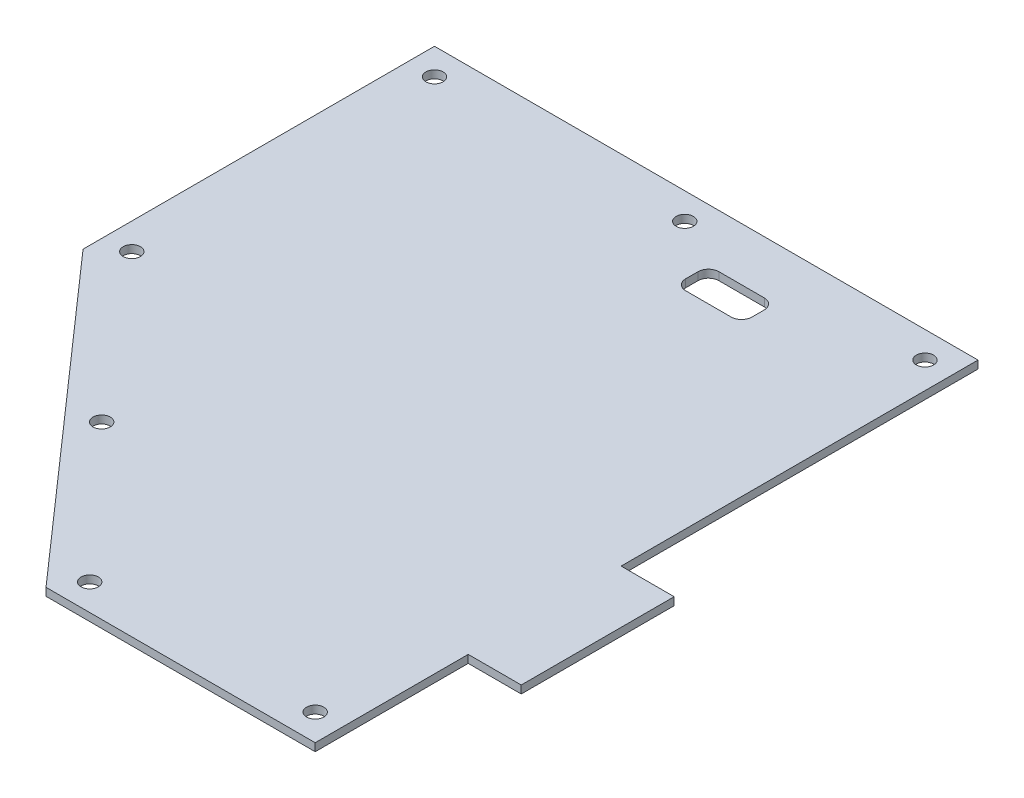
SolidWorks part; units mm, degrees
ref_plane "Front Plane" through (0, 0, 0) normal (0, 0, 1) x (1, 0, 0)
ref_plane "Top Plane" through (0, 0, 0) normal (0, 1, 0) x (1, 0, 0)
ref_plane "Right Plane" through (0, 0, 0) normal (1, 0, 0) x (0, 0, -1)
sketch "Sketch1" plane through (0, 0, 0) normal (0, 1, 0) x (1, 0, 0)
  line L0 (0, 0) -> (104.14, 0)
  line L2 (0, 0) -> (0, -67.34)
  line L4 (104.1401, -97.6797) -> (104.1401, -126.9997)
  line L5 (104.1401, -126.9997) -> (52.5601, -126.9997)
  line L6 (0, -67.34) -> (52.5601, -126.9997)
  line L8 (114.3001, -97.6797) -> (114.3001, -68.3797)
  line L11 (104.14, 0) -> (104.1401, -68.3797)
  line L12 (104.1401, -97.6797) -> (114.3001, -97.6797)
  line L13 (104.1401, -68.3797) -> (114.3001, -68.3797)
  dimension "D1" = 104.14
  dimension "D2" = 138.62
  dimension "D3" = 67.34
  dimension "D5" = 29.32
  dimension "D6" = 51.58
  dimension "D8" = 29.3
  dimension "D9" = 79.51
extrude "Boss-Extrude1" add sketch "Sketch1" along normal blind 1.5
sketch "Sketch2" plane through (0, 1.5, 0) normal (0, 1, 0) x (1, 0, 0)
  line L2 (104.1401, -126.9997) -> (104.1401, -97.6797) construction
  line L3 (52.5601, -126.9997) -> (104.1401, -126.9997) construction
  line L5 (104.14, 0) -> (0, 0) construction
  line L6 (0, 0) -> (0, -67.34) construction
  line L7 (0, -67.34) -> (52.5601, -126.9997) construction
  line L8 (104.1401, -68.3797) -> (104.14, 0) construction
  point P5 (99.0601, -121.9197)
  point P10 (55.8501, -121.9197)
  point P11 (99.06, -5.08)
  point P16 (5.08, -5.08)
  point P19 (53.03, -5.08)
  point P20 (5.08, -63.08)
  point P23 (30.4656, -94.2361)
  dimension "D2" = 5.08
  dimension "D3" = 5.08
  dimension "D4" = 5.08
  dimension "D5" = 43.21
  dimension "D6" = 5.08
  dimension "D8" = 5.08
  dimension "D9" = 5.08
  dimension "D10" = 5.08
  dimension "D11" = 47.95
  dimension "D12" = 58
  dimension "D13" = 5.08
  dimension "D14" = 37.56
  dimension "D15" = 5.08
hole_wizard "Ø4.0mm Dowel Hole1" positions "3DSketch1" profile "Sketch3" hole size "Ø4.0" standard "ANSI Metric"
sketch3d "3DSketch1"
  point P0 (5.08, 1.5, 5.08)
  point P3 (53.03, 1.5, 5.08)
  point P6 (99.06, 1.5, 5.08)
  point P12 (99.0601, 1.5, 121.9197)
  point P15 (55.8501, 1.5, 121.9197)
  point P18 (30.4656, 1.5, 94.2361)
  point P21 (5.08, 1.5, 63.08)
sketch "Sketch3" plane through (5.08, 1.5, 5.08) normal (1, 0, 0) x (0, 0, 1)
  line L0 (0, 0) -> (0, 1.5)
  line L1 (0, 1.5) -> (1.65, 1.5)
  line L2 (1.65, 1.5) -> (1.65, 0)
  line L5 (1.65, 0) -> (0, 0)
  line L10 (0, 1.5) -> (-1.65, 1.5) construction
  line L11 (0, -6.35) -> (0, 107.95) construction
  dimension "Hole Dia." = 3.3
  dimension "Hole Depth" = 1.5
  dimension "Drill Angle" = 180
sketch "Sketch4" plane through (0, 1.5, 0) normal (0, 1, 0) x (1, 0, 0)
  line L0 (104.14, 0) -> (0, 0) construction
  line L1 (0, 0) -> (0, -67.34) construction
  line L3 (62.65, -10.16) -> (75.35, -10.16)
  line L4 (62.65, -10.16) -> (62.65, -16.51)
  line L5 (62.65, -16.51) -> (75.35, -16.51)
  line L6 (75.35, -10.16) -> (75.35, -16.51)
  line L7 (62.65, -10.16) -> (75.35, -16.51) construction
  line L8 (62.65, -16.51) -> (75.35, -10.16) construction
  point P0 (69, -13.335)
  point P5 (69, -13.335)
  dimension "D1" = 13.335
  dimension "D2" = 69
  dimension "D3" = 6.35
  dimension "D4" = 12.7
extrude "Cut-Extrude1" cut sketch "Sketch4" against normal up to surface (1.5 mm away) up to face at (5.08, 0, 6.73)
fillet "Fillet1" radius 2 4 edges at (62.65, 0.75, 10.16) (75.35, 0.75, 10.16) (75.35, 0.75, 16.51) (62.65, 0.75, 16.51)
